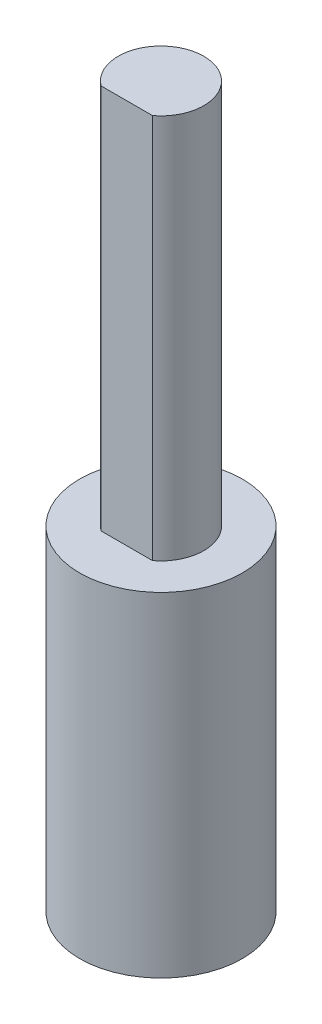
SolidWorks part; units mm, degrees
ref_plane "前视基准面" through (0, 0, 0) normal (0, 0, 1) x (1, 0, 0)
ref_plane "上视基准面" through (0, 0, 0) normal (0, 1, 0) x (1, 0, 0)
ref_plane "右视基准面" through (0, 0, 0) normal (1, 0, 0) x (0, 0, -1)
other "Configuration Table"
sketch "草图1" plane through (0, 0, 0) normal (0, 1, 0) x (1, 0, 0)
  circle A0 centre (0, 0) radius 4.75
  dimension "D1" = 9.5
extrude "凸台-拉伸1" add sketch "草图1" along normal blind 19.5
sketch "草图2" plane through (0, 19.5, 0) normal (0, 1, 0) x (1, 0, 0)
  line L0 (-1.5, -2) -> (1.5, -2)
  circle A0 centre (0, 0) radius 2.5
  dimension "D1" = 5
  dimension "D2" = 2
extrude "凸台-拉伸2" add sketch "草图2" along normal blind 22.5 contours L0 A0
